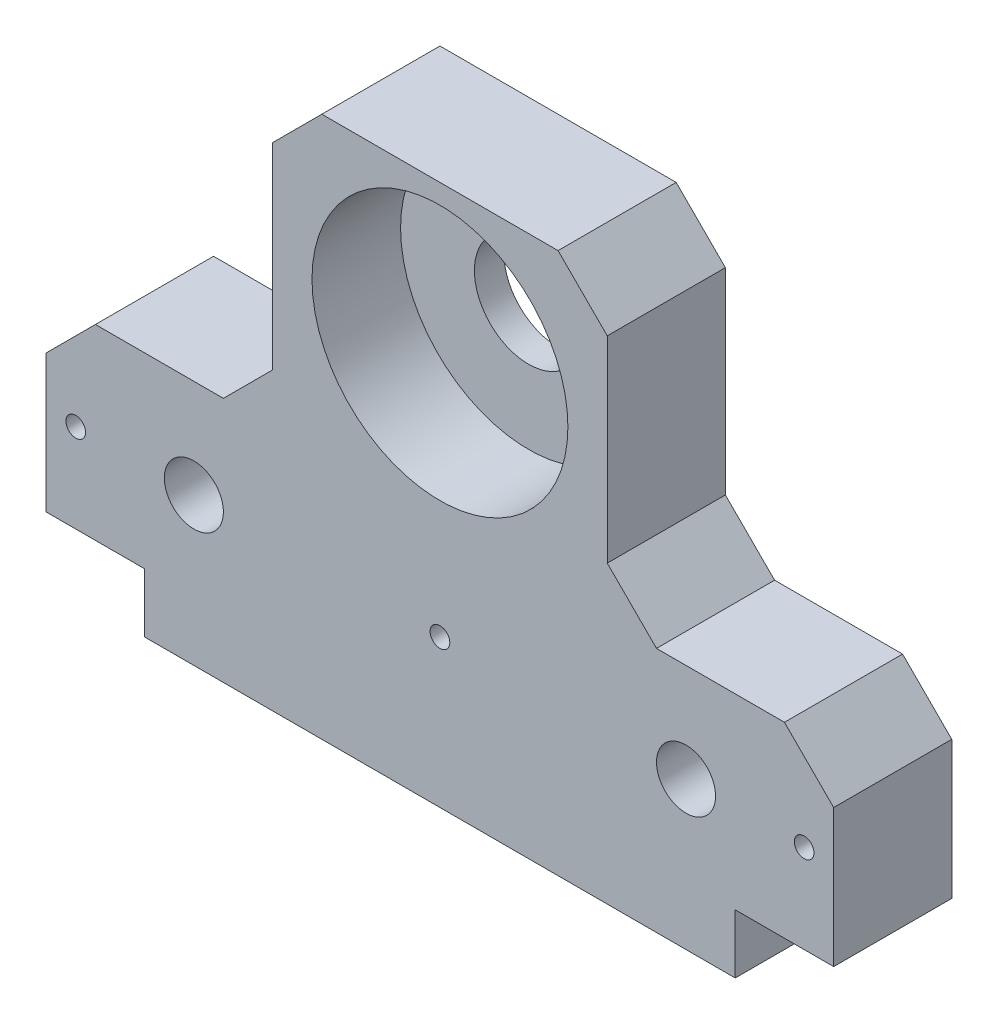
SolidWorks part; units mm, degrees
ref_plane "Plan de face" through (0, 0, 0) normal (0, 0, 1) x (1, 0, 0)
ref_plane "Plan de dessus" through (0, 0, 0) normal (0, 1, 0) x (1, 0, 0)
ref_plane "Plan de droite" through (0, 0, 0) normal (1, 0, 0) x (0, 0, -1)
sketch "Esquisse1" plane through (0, 0, 0) normal (0, 0, 1) x (1, 0, 0)
  line L0 (0, 0) -> (0, 55) construction
  line L1 (-40, 0) -> (40, 0)
  line L2 (40, 0) -> (40, 25)
  line L3 (40, 25) -> (17, 25)
  line L4 (17, 25) -> (17, 55)
  line L5 (17, 55) -> (-17, 55)
  line L6 (-17, 25) -> (-17, 55)
  line L7 (-40, 25) -> (-17, 25)
  line L8 (-40, 0) -> (-40, 25)
  line L9 (17, 40) -> (0, 40) construction
  circle A0 centre (0, 40) radius 13
  dimension "D4" = 26
  dimension "D5" = 40
  dimension "D1" = 80
  dimension "D2" = 34
  dimension "D3" = 30
extrude "Boss.-Extru.1" add sketch "Esquisse1" along normal blind 12
sketch "Esquisse2" plane through (0, 0, 12) normal (0, 0, 1) x (1, 0, 0)
  circle A0 centre (0, 40) radius 13
  circle A1 centre (0, 40) radius 5.5
  dimension "D1" = 26
  dimension "D2" = 11
extrude "Boss.-Extru.2" add sketch "Esquisse2" along normal blind 3 from vertex at -12 starting at point (17, 55, 0)
sketch "Esquisse4" plane through (0, 0, 0) normal (0, 0, -1) x (-1, 0, 0)
  line L0 (0, 0) -> (0, 55) construction
  line L1 (-17, 55) -> (17, 55) construction
  line L3 (40, 0) -> (-40, 0) construction
  line L4 (-40, 0) -> (-40, 25) construction
  circle A0 centre (-25, 15) radius 8
  circle A1 centre (25, 15) radius 8
  dimension "D1" = 16
  dimension "D2" = 15
  dimension "D3" = 15
extrude "Enlèv. mat.-Extru.2" cut sketch "Esquisse4" against normal blind 6
sketch "Esquisse5" plane through (0, 0, 6) normal (0, 0, -1) x (-1, 0, 0)
  line L0 (0, 0) -> (0, 55) construction
  line L1 (40, 0) -> (-40, 0) construction
  line L2 (-17, 55) -> (17, 55) construction
  circle A0 centre (-25, 15) radius 3
  circle A1 centre (25, 15) radius 3
  dimension "D1" = 6
extrude "Enlèv. mat.-Extru.3" cut sketch "Esquisse5" against normal through all
sketch "Esquisse6" plane through (0, 0, 12) normal (0, 0, 1) x (1, 0, 0)
  line L0 (0, 0) -> (0, 7.1495) construction
  line L1 (30, 0) -> (30, 6)
  line L2 (-40, 0) -> (-30, 0)
  line L3 (-40, 0) -> (-40, 6)
  line L4 (-40, 6) -> (-30, 6)
  line L5 (-30, 0) -> (-30, 6)
  line L6 (40, 6) -> (30, 6)
  line L7 (40, 0) -> (40, 6)
  line L8 (40, 0) -> (30, 0)
  dimension "D1" = 6
  dimension "D2" = 10
extrude "Enlèv. mat.-Extru.4" cut sketch "Esquisse6" against normal up to vertex (12 mm away) up to point (40, 0, 0)
chamfer "Chanfrein1" distance 5 angle 45 6 edges at (40, 25, 6) (17, 25, 6) (-17, 25, 6) (-40, 25, 6) (17, 55, 6) (-17, 55, 6)
sketch "Esquisse7" plane through (0, 0, 0) normal (0, 0, -1) x (-1, 0, 0)
  line L0 (0, 0) -> (0, 55) construction
  line L1 (-12, 55) -> (12, 55) construction
  line L2 (0, 15) -> (-37, 15) construction
  line L3 (30, 0) -> (-30, 0) construction
  circle A0 centre (-10, 45) radius 1
  circle A1 centre (10, 45) radius 1
  circle A2 centre (-37, 15) radius 1
  circle A3 centre (37, 15) radius 1
  circle A4 centre (0, 15) radius 1
  dimension "D3" = 2
  dimension "D1" = 10
  dimension "D2" = 10
  dimension "D4" = 15
  dimension "D5" = 37
extrude "Enlèv. mat.-Extru.5" cut sketch "Esquisse7" against normal up to vertex (12 mm away) up to point (-35, 25, 12)
